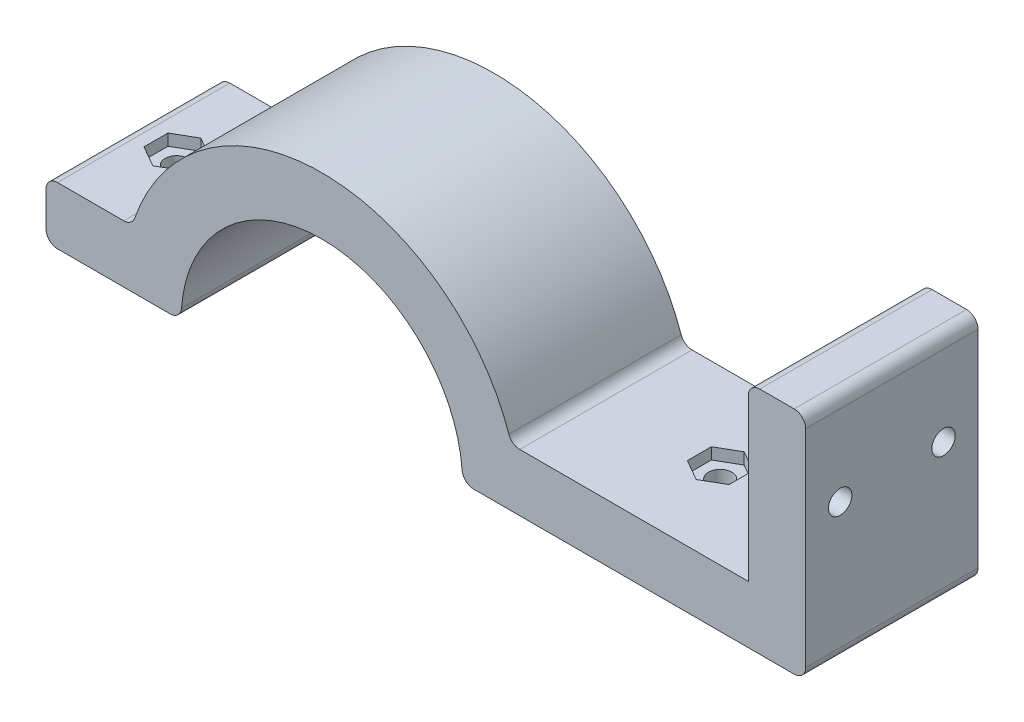
SolidWorks part; units mm, degrees
ref_plane "Front Plane" through (0, 0, 0) normal (0, 0, 1) x (1, 0, 0)
ref_plane "Top Plane" through (0, 0, 0) normal (0, 1, 0) x (1, 0, 0)
ref_plane "Right Plane" through (0, 0, 0) normal (1, 0, 0) x (0, 0, -1)
sketch "Sketch1" plane through (0, 0, 0) normal (0, 0, 1) x (1, 0, 0)
  line L0 (-62.23, 0) -> (0, 0) construction
  line L5 (0, 0) -> (75.8825, 0)
  line L6 (63.1825, 12.7) -> (63.1825, 50.8)
  line L7 (63.1825, 50.8) -> (75.8825, 50.8)
  line L8 (75.8825, 0) -> (75.8825, 50.8)
  line L9 (75.8825, 0) -> (0, 0)
  line L11 (63.1825, 12.7) -> (0, 12.7) construction
  line L12 (0, 0) -> (0, 12.7) construction
  line L13 (10.819, 12.7) -> (63.1825, 12.7)
  line L14 (-62.23, 0) -> (-92.099, 0)
  line L16 (-73.049, 12.7) -> (-92.099, 12.7)
  line L17 (-92.099, 0) -> (-92.099, 12.7)
  arc A0 (0, 0) -> (-62.23, 0) centre (-31.115, 0) ccw
  arc A1 (-73.049, 12.7) -> (10.819, 12.7) centre (-31.115, 0) cw
  dimension "D4" = 62.23
  dimension "D7" = 12.7
  dimension "D1" = 12.7
  dimension "D2" = 63.1825
  dimension "D3" = 50.8
  dimension "D5" = 19.05
  dimension "D6" = 12.7
extrude "Boss-Extrude1" add sketch "Sketch1" along normal blind 38.1 contours A1 L16 L17 L14 A0 L5 L8 L7 L6 L13
fillet "Fillet1" radius 2.54 9 edges at (-92.099, 0, 19.05) (-92.099, 12.7, 19.05) (63.1825, 50.8, 19.05) (75.8825, 50.8, 19.05) (75.8825, 0, 19.05) (0, 0, 19.05) (-62.23, 0, 19.05) (10.819, 12.7, 19.05) (-73.049, 12.7, 19.05)
sketch "Sketch3" plane through (0, 12.7, 0) normal (0, 1, 0) x (1, 0, 0)
  line L0 (37.9228, -38.1) -> (37.9228, 0) construction
  line L1 (12.6632, -38.1) -> (63.1825, -38.1) construction
  line L2 (12.6632, 0) -> (63.1825, 0) construction
  line L3 (12.6632, 0) -> (12.6632, -38.1) construction
  line L4 (33.3254, -16.3957) -> (33.3254, -21.7043)
  line L5 (33.3254, -21.7043) -> (37.9228, -24.3586)
  line L6 (37.9228, -24.3586) -> (42.5202, -21.7043)
  line L7 (42.5202, -21.7043) -> (42.5202, -16.3957)
  line L8 (42.5202, -16.3957) -> (37.9228, -13.7414)
  line L9 (37.9228, -13.7414) -> (33.3254, -16.3957)
  line L10 (-82.2261, -38.1) -> (-82.2261, 0) construction
  line L11 (-74.8932, -38.1) -> (-89.559, -38.1) construction
  line L12 (-74.8932, 0) -> (-89.559, 0) construction
  line L14 (-82.2261, -13.7414) -> (-86.8235, -16.3957)
  line L15 (-86.8235, -16.3957) -> (-86.8235, -21.7043)
  line L16 (-86.8235, -21.7043) -> (-82.2261, -24.3586)
  line L17 (-82.2261, -24.3586) -> (-77.6287, -21.7043)
  line L18 (-77.6287, -21.7043) -> (-77.6287, -16.3957)
  line L19 (-77.6287, -16.3957) -> (-82.2261, -13.7414)
  circle A0 centre (37.9228, -19.05) radius 4.5974 construction
  circle A1 centre (-82.2261, -19.05) radius 4.5974 construction
  dimension "D1" = 9.1948
extrude "Cut-Extrude1" cut sketch "Sketch3" against normal blind 2.54
hole_wizard "#6 (0.204) Diameter Hole1" positions "Sketch4" profile "Sketch5" hole size "#6" standard "ANSI Inch"
sketch "Sketch4" plane through (0, 12.7, 0) normal (0, 1, 0) x (1, 0, 0)
  line L0 (35.6241, -23.0315) -> (40.2215, -15.0685)
  line L1 (33.3254, -21.7043) -> (37.9228, -24.3586) construction
  line L2 (42.5202, -16.3957) -> (37.9228, -13.7414) construction
  line L4 (-84.5248, -23.0315) -> (-79.9274, -15.0685)
  line L5 (-86.8235, -21.7043) -> (-82.2261, -24.3586) construction
  line L6 (-77.6287, -16.3957) -> (-82.2261, -13.7414) construction
  point P17 (37.9228, -19.05)
  point P19 (-82.2261, -19.05)
sketch "Sketch5" plane through (-82.2261, 12.7, 19.05) normal (1, 0, 0) x (0, 0, 1)
  line L0 (0, 0) -> (0, 14.2567)
  line L1 (0, 14.2567) -> (2.5908, 12.7)
  line L2 (2.5908, 12.7) -> (2.5908, 0)
  line L5 (2.5908, 0) -> (0, 0)
  line L10 (0, 14.2567) -> (-2.5908, 12.7) construction
  line L11 (0, -6.35) -> (0, 107.95) construction
  dimension "Hole Dia." = 5.1816
  dimension "Hole Depth" = 12.7
  dimension "Drill Angle" = 118
sketch "Sketch6" plane through (63.1825, 0, 0) normal (-1, 0, 0) x (0, 0, 1)
  line L0 (0, 30.48) -> (7.62, 30.48) construction
  line L3 (0, 12.7) -> (0, 48.26) construction
  line L4 (7.62, 30.48) -> (30.48, 30.48) construction
  line L5 (30.48, 30.48) -> (38.1, 30.48) construction
  line L6 (38.1, 12.7) -> (38.1, 48.26) construction
  line L8 (12.3504, 28.0708) -> (12.0717, 33.3721)
  line L9 (12.0717, 33.3721) -> (7.3412, 35.7813)
  line L10 (7.3412, 35.7813) -> (2.8896, 32.8892)
  line L11 (2.8896, 32.8892) -> (3.1683, 27.5879)
  line L12 (3.1683, 27.5879) -> (7.8988, 25.1787)
  line L13 (7.8988, 25.1787) -> (12.3504, 28.0708)
  line L14 (35.2104, 28.0708) -> (34.9317, 33.3721)
  line L15 (34.9317, 33.3721) -> (30.2012, 35.7813)
  line L16 (30.2012, 35.7813) -> (25.7496, 32.8892)
  line L17 (25.7496, 32.8892) -> (26.0283, 27.5879)
  line L18 (26.0283, 27.5879) -> (30.7588, 25.1787)
  line L19 (30.7588, 25.1787) -> (35.2104, 28.0708)
  circle A0 centre (7.62, 30.48) radius 4.5974 construction
  circle A1 centre (30.48, 30.48) radius 4.5974 construction
  dimension "D1" = 9.1948
  dimension "D2" = 22.86
extrude "Cut-Extrude2" cut sketch "Sketch6" against normal blind 2.54
hole_wizard "#6 (0.204) Diameter Hole2" positions "Sketch7" profile "Sketch8" hole size "#6" standard "ANSI Inch"
sketch "Sketch7" plane through (65.7225, 0, 0) normal (-1, 0, 0) x (0, 0, 1)
  line L0 (9.7065, 34.5767) -> (5.5335, 26.3833)
  line L1 (12.0717, 33.3721) -> (7.3412, 35.7813) construction
  line L2 (3.1683, 27.5879) -> (7.8988, 25.1787) construction
  line L4 (32.5665, 34.5767) -> (28.3935, 26.3833)
  line L5 (34.9317, 33.3721) -> (30.2012, 35.7813) construction
  line L6 (26.0283, 27.5879) -> (30.7588, 25.1787) construction
  point P18 (7.62, 30.48)
  point P20 (30.48, 30.48)
sketch "Sketch8" plane through (65.7225, 30.48, 30.48) normal (0, 1, 0) x (0, 0, 1)
  line L0 (0, 0) -> (0, 14.2567)
  line L1 (0, 14.2567) -> (2.5908, 12.7)
  line L2 (2.5908, 12.7) -> (2.5908, 0)
  line L5 (2.5908, 0) -> (0, 0)
  line L10 (0, 14.2567) -> (-2.5908, 12.7) construction
  line L11 (0, -6.35) -> (0, 107.95) construction
  dimension "Hole Dia." = 5.1816
  dimension "Hole Depth" = 12.7
  dimension "Drill Angle" = 118
